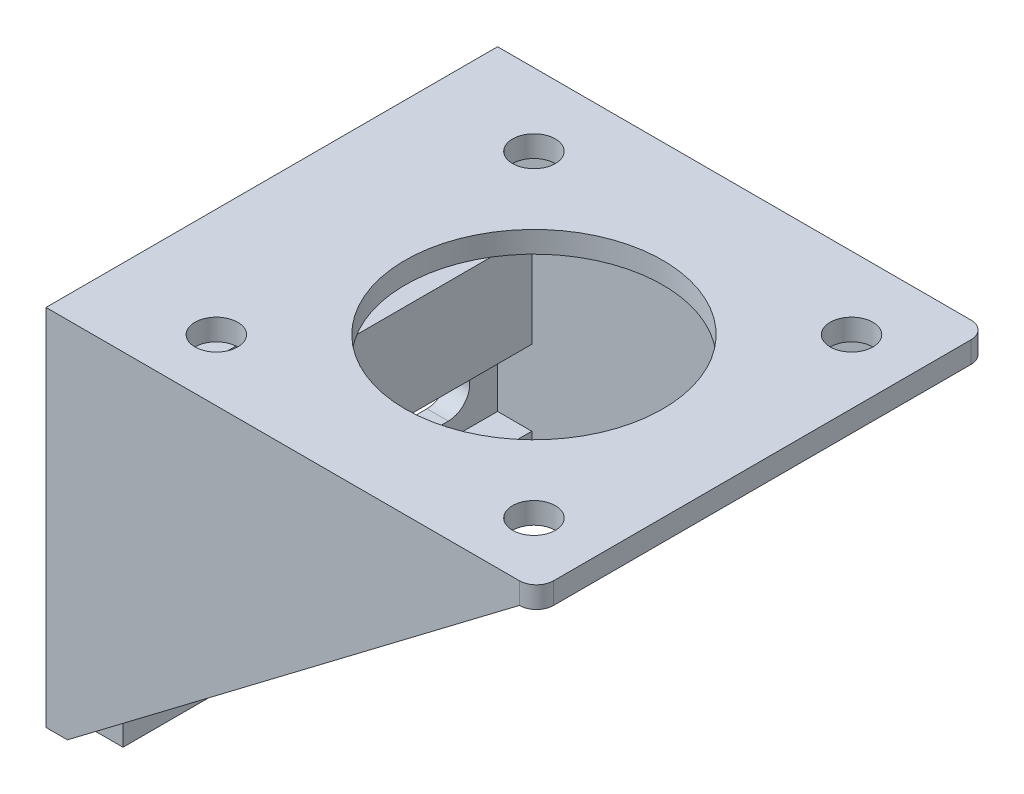
SolidWorks part; units mm, degrees
ref_plane "Front Plane" through (0, 0, 0) normal (0, 0, 1) x (1, 0, 0)
ref_plane "Top Plane" through (0, 0, 0) normal (0, 1, 0) x (1, 0, 0)
ref_plane "Right Plane" through (0, 0, 0) normal (1, 0, 0) x (0, 0, -1)
sketch "Sketch1" plane through (0, 0, 0) normal (0, 1, 0) x (1, 0, 0)
  line L0 (-26.2255, 26.2255) -> (-26.2255, -26.2255) construction
  line L1 (-26.2255, -26.2255) -> (26.2255, -26.2255) construction
  line L2 (26.2255, -26.2255) -> (26.2255, 26.2255) construction
  line L3 (26.2255, 26.2255) -> (-26.2255, 26.2255) construction
  line L4 (-26.2255, 26.2255) -> (26.2255, -26.2255) construction
  line L5 (-39.6875, 34.29) -> (33.0835, 34.29)
  line L6 (33.0835, 34.29) -> (33.0835, -32.7025)
  line L7 (33.0835, -32.7025) -> (-39.6875, -32.7025)
  line L8 (-39.6875, -32.7025) -> (-39.6875, 34.29)
  line L9 (-23.5585, 23.5585) -> (23.5585, 23.5585) construction
  line L10 (23.5585, 23.5585) -> (23.5585, -23.5585) construction
  line L11 (23.5585, -23.5585) -> (-23.5585, -23.5585) construction
  line L12 (-23.5585, -23.5585) -> (-23.5585, 23.5585) construction
  line L13 (26.7335, 27.5945) -> (26.7335, 19.7469) construction
  circle A0 centre (0, 0) radius 19.1135
  circle A1 centre (-23.5585, 23.5585) radius 2.667 construction
  circle A2 centre (23.5585, 23.5585) radius 2.667 construction
  circle A3 centre (-23.5585, -23.5585) radius 2.667 construction
  circle A4 centre (23.5585, -23.5585) radius 2.667 construction
  circle A5 centre (-23.5585, 23.5585) radius 3.175
  circle A6 centre (23.5585, 23.5585) radius 3.175
  circle A7 centre (23.5585, -23.5585) radius 3.175
  circle A8 centre (-23.5585, -23.5585) radius 3.175
  point P13 (0, 0)
  dimension "D1" = 38.227
  dimension "D2" = 5.334
  dimension "D8" = 6.35
  dimension "D3" = 52.451
  dimension "D5" = 34.29
  dimension "D6" = 32.7025
  dimension "D7" = 39.6875
  dimension "D4" = 6.35
extrude "Boss-Extrude1" add sketch "Sketch1" along normal blind 3.175
fillet "Fillet1" radius 2.54 2 edges at (33.0835, 1.5875, 32.7025) (33.0835, 1.5875, -34.29)
sketch "Sketch2" plane through (-39.6875, 0, 0) normal (-1, 0, 0) x (0, 0, 1)
  line L0 (-34.29, 0) -> (-34.29, -50.8)
  line L2 (32.7025, -50.8) -> (32.7025, 0)
  line L3 (-34.29, 0) -> (32.7025, 0)
  line L4 (32.7025, -50.8) -> (-34.29, -50.8)
  line L5 (-0.7938, 0) -> (-0.7938, -50.8) construction
  point P6 (-0.7938, -50.8)
  dimension "D1" = 50.8
extrude "Boss-Extrude2" add sketch "Sketch2" against normal blind 3.175
ref_plane "Plane1" through (-36.5125, 0, -34.29) normal (0, -1, 0) x (-1, 0, 0)
sketch "Sketch7" plane through (0, 0, 32.7025) normal (0, 0, 1) x (1, 0, 0)
  line L0 (-36.5125, -50.8) -> (30.5435, 0)
  line L1 (30.5435, 0) -> (-36.5125, 0)
  line L2 (-91.5125, 0) -> (18.4875, 0) construction
  line L3 (-36.5125, 0) -> (-36.5125, -50.8)
extrude "Boss-Extrude5" add sketch "Sketch7" against normal blind 3.175
sketch "Sketch8" plane through (0, 0, -34.29) normal (0, 0, -1) x (-1, 0, 0)
  line L0 (-30.5435, 0) -> (36.5125, 0)
  line L1 (36.5125, 0) -> (36.5125, -50.8)
  line L2 (36.5125, -50.8) -> (-30.5435, 0)
extrude "Boss-Extrude6" add sketch "Sketch8" against normal blind 3.175
sketch "Sketch9" plane through (-36.5125, 0, 0) normal (1, 0, 0) x (0, 0, -1)
  line L0 (-12.3825, -9.525) -> (23.8125, -9.525) construction
  line L1 (23.8125, -9.525) -> (23.8125, -34.925) construction
  line L2 (23.8125, -34.925) -> (-12.3825, -34.925) construction
  line L3 (-12.3825, -34.925) -> (-12.3825, -9.525) construction
  line L6 (-2.2225, -6.35) -> (-12.3825, -6.35)
  line L7 (-2.2225, -12.7) -> (-12.3825, -12.7)
  line L8 (-2.2225, -31.75) -> (-12.3825, -31.75)
  line L9 (-2.2225, -38.1) -> (-12.3825, -38.1)
  line L10 (23.8125, -38.1) -> (13.6525, -38.1)
  line L11 (23.8125, -31.75) -> (13.6525, -31.75)
  line L12 (23.8125, -6.35) -> (13.6525, -6.35)
  line L13 (23.8125, -12.7) -> (13.6525, -12.7)
  line L14 (-30.1625, 3.175) -> (31.75, 3.175) construction
  circle A0 centre (23.8125, -9.525) radius 3.175
  circle A1 centre (-12.3825, -9.525) radius 3.175
  circle A2 centre (23.8125, -34.925) radius 3.175
  circle A3 centre (-12.3825, -34.925) radius 3.175
  circle A4 centre (-2.2225, -9.525) radius 3.175
  circle A5 centre (13.6525, -9.525) radius 3.175
  circle A6 centre (13.6525, -34.925) radius 3.175
  circle A7 centre (-2.2225, -34.925) radius 3.175
  point P10 (0, 0)
  dimension "D1" = 6.35
  dimension "D2" = 12.3825
  dimension "D3" = 25.4
  dimension "D4" = 10.16
  dimension "D5" = 10.16
  dimension "D6" = 12.7
  dimension "D7" = 26.035
extrude "Cut-Extrude1" cut sketch "Sketch9" against normal blind 3.175 contours A4 L6 A1 L7 | A4 | A1 | A5 L13 A0 L12 | A5 | A0 | A2 | A6 L10 A2 L11 | A6 | A7 | A7 L8 A3 L9 | A3
sketch "Sketch10" plane through (-36.5125, 0, 0) normal (1, 0, 0) x (0, 0, -1)
  line L0 (-29.5275, 0) -> (31.115, 0)
  line L1 (31.115, 0) -> (31.115, -3.937)
  line L2 (31.115, 0) -> (31.115, -50.8) construction
  line L3 (31.115, -3.937) -> (-29.5275, -3.937)
  line L4 (-29.5275, 0) -> (-29.5275, -50.8) construction
  line L5 (-29.5275, -3.937) -> (-29.5275, 0)
  line L6 (31.115, -15.113) -> (-29.5275, -15.113)
  line L7 (31.115, -50.8) -> (31.115, 0) construction
  line L8 (-29.5275, -50.8) -> (-29.5275, 0) construction
  line L9 (-29.5275, -15.113) -> (-29.5275, -29.337)
  line L10 (-29.5275, -29.337) -> (31.115, -29.337)
  line L11 (23.8125, -9.525) -> (23.8125, -3.937)
  line L12 (23.8125, -9.525) -> (23.8125, -15.113)
  line L13 (-29.5275, -40.513) -> (31.115, -40.513)
  line L14 (31.115, -40.513) -> (31.115, -50.8)
  line L15 (31.115, -50.8) -> (-29.5275, -50.8)
  line L16 (-29.5275, -50.8) -> (-29.5275, -40.513)
  line L17 (23.8125, -34.925) -> (23.8125, -29.337)
  line L18 (23.8125, -34.925) -> (23.8125, -40.513)
  line L19 (31.115, -29.337) -> (31.115, -15.113)
  line M29 (31.115, -50.8) -> (31.115, 0)
  line M30 (31.115, 0) -> (-29.5275, 0)
  line M31 (-29.5275, 0) -> (-29.5275, -50.8)
  line M32 (-29.5275, -50.8) -> (31.115, -50.8)
  dimension "D1" = 11.176
  dimension "D2" = 11.176
extrude "Boss-Extrude7" add sketch "Sketch10" along normal blind 5.08 contours L10 L6 M31 M29 | L3 M29 M30 M31 | L13 M31 M32 M29
equation "\"D5@Sketch1\"=1.1+1/8+2/16"
equation "\"D6@Sketch1\"=1.1+1/8+1/16"
equation "\"D2@Sketch10\"=\"D1@Sketch10\""
